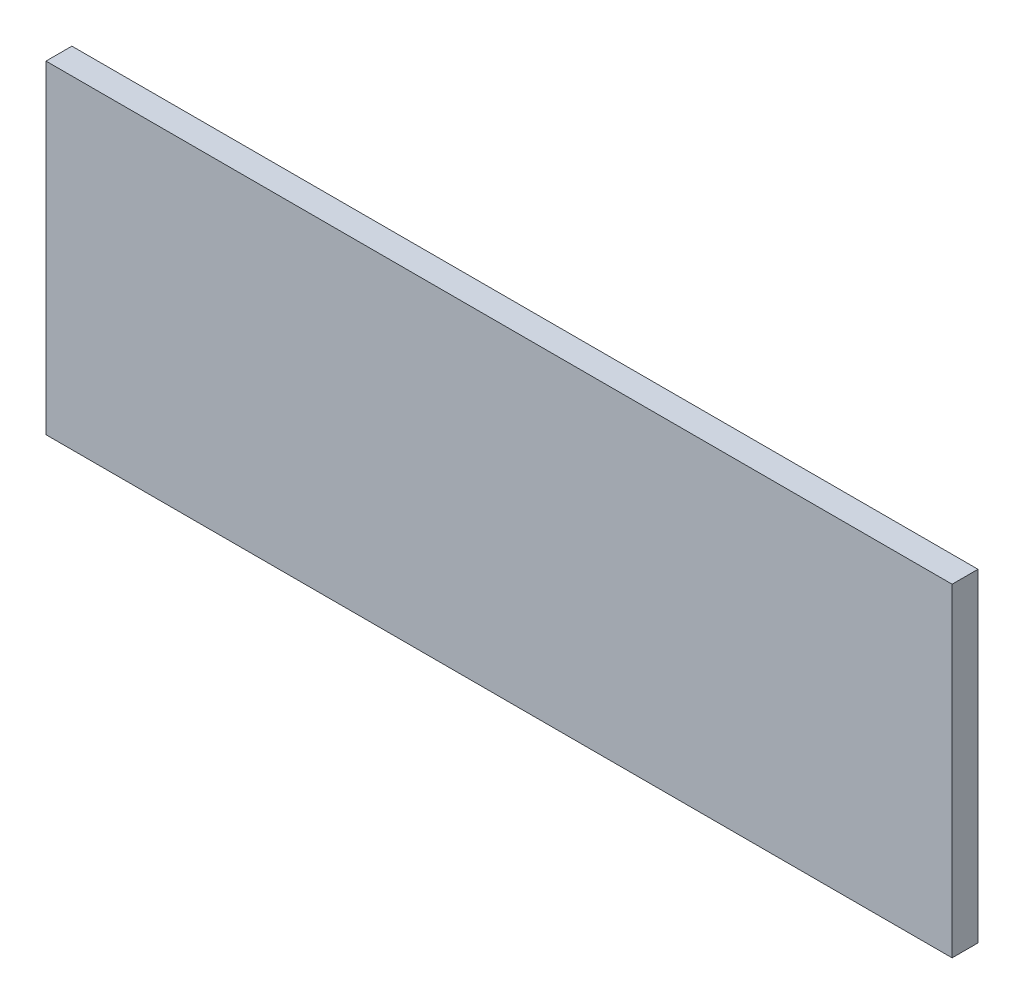
SolidWorks part; units mm, degrees
ref_plane "前视" through (0, 0, 0) normal (0, 0, 1) x (1, 0, 0)
ref_plane "上视" through (0, 0, 0) normal (0, 1, 0) x (1, 0, 0)
ref_plane "右视" through (0, 0, 0) normal (1, 0, 0) x (0, 0, -1)
sketch "草图1" plane through (0, 0, 0) normal (0, 0, 1) x (1, 0, 0)
  line L0 (0, -309.0802) -> (0, 309.0802) construction
  line L1 (-350, -125) -> (350, -125)
  line L2 (-350, -125) -> (-350, 125)
  line L3 (-350, 125) -> (350, 125)
  line L4 (350, -125) -> (350, 125)
  line L5 (-416.575, 0) -> (416.575, 0) construction
  line L6 (-60, 231.9077) -> (-60, -177.8082) construction
  line L7 (-405.3499, 80) -> (106.7949, 80) construction
  line L8 (-300, 281.0174) -> (-300, -177.8082) construction
  line L9 (-140, 189.8136) -> (-140, -190.9976) construction
  line L10 (-220, 297.8551) -> (-220, -190.9976) construction
  circle A0 centre (-300, 80) radius 13
  circle A1 centre (-220, 80) radius 13
  circle A2 centre (-140, 80) radius 13
  circle A3 centre (-60, 80) radius 13
  circle A4 centre (-60, 0) radius 13
  circle A5 centre (-220, 0) radius 13
  circle A6 centre (-300, 0) radius 13
  circle A7 centre (-140, 0) radius 13
  circle A8 centre (-60, -80) radius 13
  circle A9 centre (-140, -80) radius 13
  circle A10 centre (-220, -80) radius 13
  circle A11 centre (-300, -80) radius 13
  circle A12 centre (300, -80) radius 13
  circle A13 centre (220, -80) radius 13
  circle A14 centre (140, -80) radius 13
  circle A15 centre (60, -80) radius 13
  circle A16 centre (140, 0) radius 13
  circle A17 centre (300, 0) radius 13
  circle A18 centre (220, 0) radius 13
  circle A19 centre (60, 0) radius 13
  circle A20 centre (60, 80) radius 13
  circle A21 centre (140, 80) radius 13
  circle A22 centre (220, 80) radius 13
  circle A23 centre (300, 80) radius 13
  dimension "D6" = 26
  dimension "D1" = 700
  dimension "D2" = 250
  dimension "D3" = 80
  dimension "D4" = 50
  dimension "D5" = 80
  dimension "D7" = 80
  dimension "D8" = 80
extrude "基体-拉伸" add sketch "草图1" along normal blind 20
sketch "草图2" plane through (0, 0, 20) normal (0, 0, 1) x (1, 0, 0)
  line L1 (-350, 125) -> (350, 125)
  line L2 (-350, 125) -> (-350, -125)
  line L3 (-350, -125) -> (350, -125)
  line L4 (350, 125) -> (350, -125)
extrude "凸台-拉伸1" add sketch "草图2" against normal blind 20
